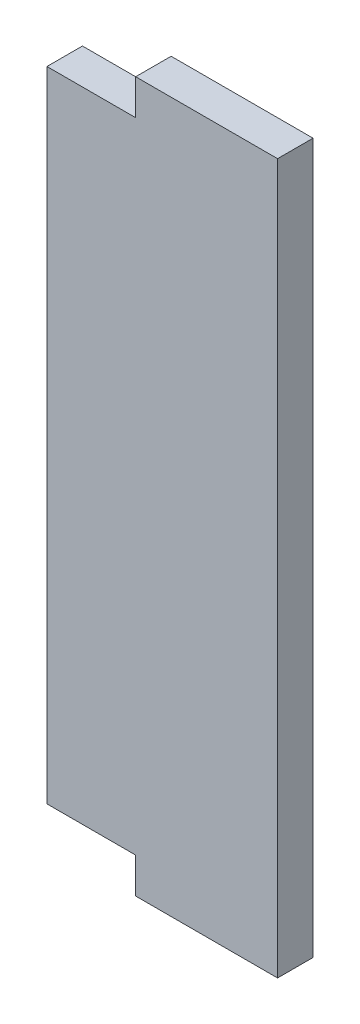
SolidWorks part; units mm, degrees
ref_plane "Front Plane" through (0, 0, 0) normal (0, 0, 1) x (1, 0, 0)
ref_plane "Top Plane" through (0, 0, 0) normal (0, 1, 0) x (1, 0, 0)
ref_plane "Right Plane" through (0, 0, 0) normal (1, 0, 0) x (0, 0, -1)
sketch "Sketch1" plane through (0, 0, 0) normal (0, 0, 1) x (1, 0, 0)
  line L0 (14.2875, 57.15) -> (14.2875, 60.325) construction
  line L1 (26.9875, -3.175) -> (6.35, -3.175)
  line L2 (26.9875, -3.175) -> (26.9875, 60.325)
  line L3 (26.9875, 60.325) -> (6.35, 60.325)
  line L4 (6.35, -3.175) -> (6.35, 60.325)
  line L5 (14.2875, -3.175) -> (6.35, -3.175)
  line L6 (14.2875, -3.175) -> (14.2875, 0)
  line L7 (14.2875, 0) -> (6.35, 0)
  line L8 (6.35, -3.175) -> (6.35, 0)
  line L9 (6.35, 60.325) -> (14.2875, 60.325)
  line L10 (6.35, 60.325) -> (6.35, 57.15)
  line L11 (6.35, 57.15) -> (14.2875, 57.15)
  line L12 (14.2875, 60.325) -> (14.2875, 57.15)
  line L13 (26.9875, 57.15) -> (14.2875, 57.15) construction
extrude "Boss-Extrude1" add sketch "Sketch1" along normal blind 3.175 contours L3 L12 L11 L4 L7 L6 L1 L2
